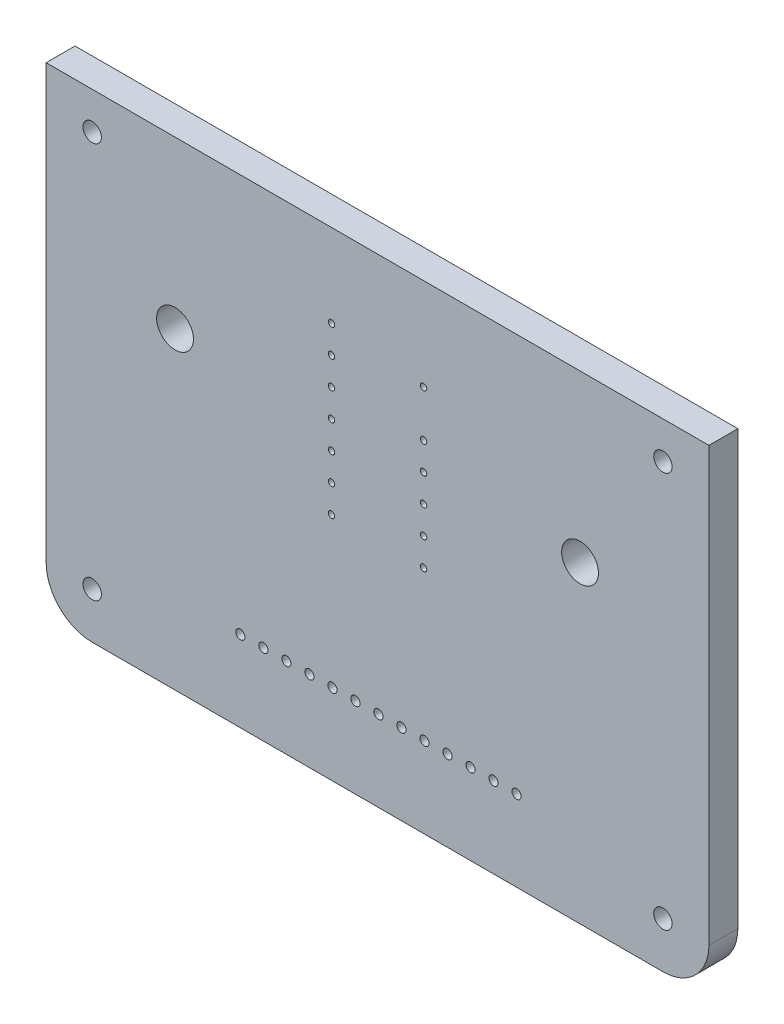
SolidWorks part; units mm, degrees
ref_plane "Plan de face" through (0, 0, 0) normal (0, 0, 1) x (1, 0, 0)
ref_plane "Plan de dessus" through (0, 0, 0) normal (0, 1, 0) x (1, 0, 0)
ref_plane "Plan de droite" through (0, 0, 0) normal (1, 0, 0) x (0, 0, -1)
ref_plane "Plan1" through (0, 0, 0) normal (0, 0, -1) x (-1, 0, 0)
sketch "Esquisse1" plane through (0, 0, 0) normal (0, 0, -1) x (-1, 0, 0)
  line L0 (0, 26.01) -> (-36, 26.01)
  line L1 (-36, 26.01) -> (-36, 0)
  line L2 (-36, 0) -> (0, 0)
  line L3 (0, 0) -> (0, 26.01)
  circle A0 centre (-15.5, 21.5) radius 0.175
  circle A1 centre (-15.5, 20) radius 0.175
  circle A2 centre (-15.5, 18.5) radius 0.175
  circle A3 centre (-15.5, 15.5) radius 0.175
  circle A4 centre (-15.5, 17) radius 0.175
  circle A5 centre (-15.5, 12.5) radius 0.175
  circle A6 centre (-15.5, 14) radius 0.175
  circle A7 centre (-7, 17) radius 0.5
  circle A8 centre (-20.5, 21) radius 0.175
  circle A9 centre (-20.5, 18.5) radius 0.175
  circle A10 centre (-20.5, 15.5) radius 0.175
  circle A11 centre (-20.5, 17) radius 0.175
  circle A12 centre (-20.5, 12.5) radius 0.175
  circle A13 centre (-20.5, 14) radius 0.175
  circle A14 centre (-2.5, 24) radius 0.5
  circle A15 centre (-29, 17) radius 0.5
  circle A16 centre (-2.5, 2.5) radius 0.5
  circle A17 centre (-33.5, 2.5) radius 0.5
  circle A18 centre (-33.5, 24) radius 0.5
  circle A19 centre (-10.55, 4.39) radius 0.25
  circle A20 centre (-13.05, 4.39) radius 0.25
  circle A21 centre (-15.55, 4.39) radius 0.25
  circle A22 centre (-25.55, 4.39) radius 0.25
  circle A23 centre (-19.3, 4.39) radius 0.25
  circle A24 centre (-21.8, 4.39) radius 0.25
  circle A25 centre (-24.3, 4.39) radius 0.25
  circle A26 centre (-23.05, 4.39) radius 0.25
  circle A27 centre (-20.55, 4.39) radius 0.25
  circle A28 centre (-18.05, 4.39) radius 0.25
  circle A29 centre (-16.8, 4.39) radius 0.25
  circle A30 centre (-14.3, 4.39) radius 0.25
  circle A31 centre (-11.8, 4.39) radius 0.25
extrude "Boss.-Extru.1" add sketch "Esquisse1" against normal blind 1.57
sketch "Esquisse2" plane through (0, 0, 1.57) normal (0, 0, 1) x (1, 0, 0)
  circle A0 centre (7, 17) radius 1
  circle A1 centre (29, 17) radius 1
  dimension "D1" = 2
  dimension "D2" = 2
extrude "Enlèv. mat.-Extru.1" cut sketch "Esquisse2" against normal up to next
fillet "Congé1" radius 2.5 2 edges at (36, 0, 0.785) (0, 0, 0.785)
